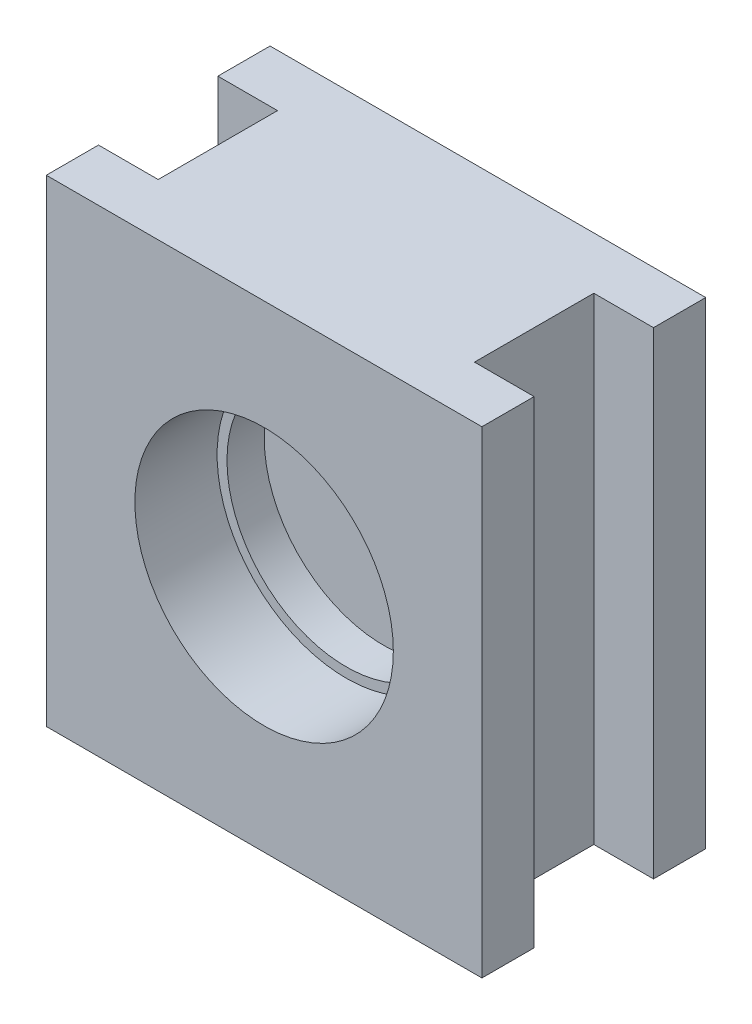
SolidWorks part; units mm, degrees
material "Gray Cast Iron (SN)"
ref_plane "Front Plane" through (0, 0, 0) normal (0, 0, 1) x (1, 0, 0)
ref_plane "Top Plane" through (0, 0, 0) normal (0, 1, 0) x (1, 0, 0)
ref_plane "Right Plane" through (0, 0, 0) normal (1, 0, 0) x (0, 0, -1)
sketch "Sketch1" plane through (0, 0, 0) normal (0, 0, 1) x (1, 0, 0)
  line L1 (13.462, 20.32) -> (-13.462, 20.32)
  line L2 (13.462, 20.32) -> (13.462, -20.32)
  line L3 (13.462, -20.32) -> (-13.462, -20.32)
  line L4 (-13.462, 20.32) -> (-13.462, -20.32)
  line L5 (13.462, 20.32) -> (-13.462, -20.32) construction
  line L6 (13.462, -20.32) -> (-13.462, 20.32) construction
  point P0 (0, 0)
  dimension "D1" = 26.924
  dimension "D2" = 40.64
extrude "Boss-Extrude1" add sketch "Sketch1" along normal blind 19.05
sketch "Sketch2" plane through (13.462, 0, 0) normal (1, 0, 0) x (0, 0, -1)
  line L0 (-19.05, -20.32) -> (0, -20.32) construction
  line L1 (-14.605, -20.32) -> (-4.445, -20.32)
  line L2 (-14.605, -20.32) -> (-14.605, 20.32)
  line L3 (-14.605, 20.32) -> (-4.445, 20.32)
  line L4 (-4.445, -20.32) -> (-4.445, 20.32)
  line L5 (-19.05, 20.32) -> (0, 20.32) construction
  line L6 (-9.525, 20.32) -> (-9.525, -20.32) construction
  line M1 (0, -20.32) -> (0, 20.32)
  line M2 (0, 20.32) -> (-19.05, 20.32)
  line M3 (-19.05, 20.32) -> (-19.05, -20.32)
  line M4 (-19.05, -20.32) -> (0, -20.32)
  dimension "D1" = 10.16
extrude "Boss-Extrude2" add sketch "Sketch2" along normal blind 5.08 contours L2 M4 M2 M3 | L4 M4 M1 M2
mirror "Mirror1" about plane through (0, 0, 0) normal (1, 0, 0) of "Boss-Extrude2"
scale "Scale1" [suppressed]
sketch "Sketch3" plane through (0, 0, 19.05) normal (0, 0, 1) x (1, 0, 0)
  circle A0 centre (0, 0) radius 11
  dimension "D1" = 22
extrude "Cut-Extrude1" cut sketch "Sketch3" against normal blind 7
sketch "Sketch4" plane through (0, 0, 12.05) normal (0, 0, 1) x (1, 0, 0)
  circle A0 centre (0, 0) radius 10.16
  dimension "D1" = 20.32
extrude "Cut-Extrude2" cut sketch "Sketch4" against normal blind 3.175
